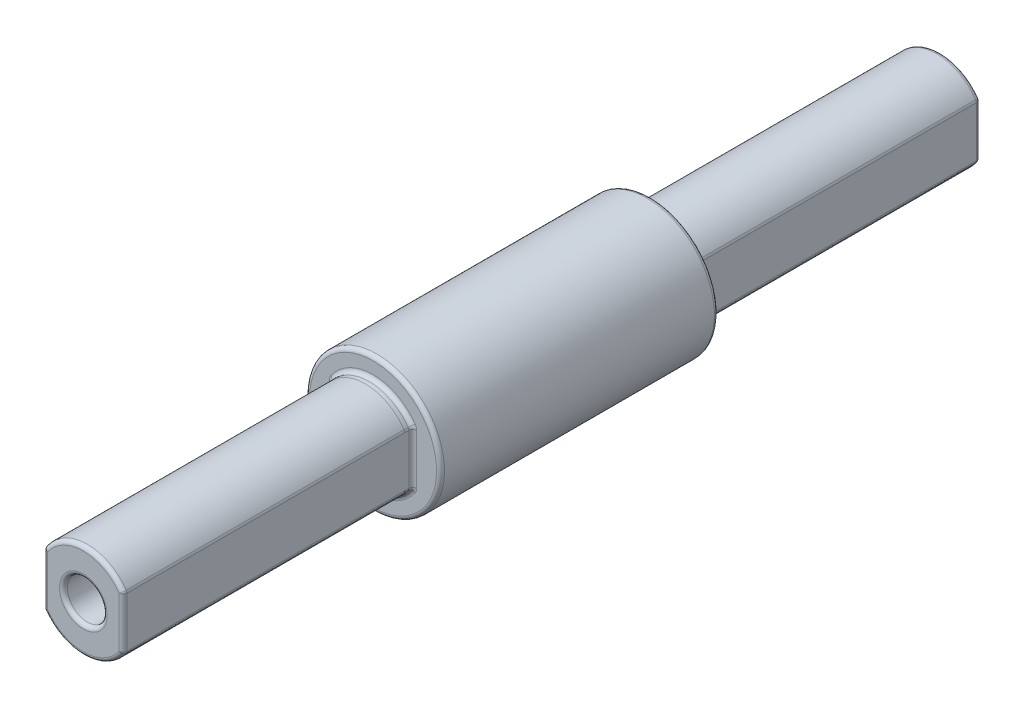
SolidWorks part; units mm, degrees
ref_plane "Alzado" through (0, 0, 0) normal (0, 0, 1) x (1, 0, 0)
ref_plane "Planta" through (0, 0, 0) normal (0, 1, 0) x (1, 0, 0)
ref_plane "Vista lateral" through (0, 0, 0) normal (1, 0, 0) x (0, 0, -1)
sketch "Croquis1" plane through (0, 0, 0) normal (1, 0, 0) x (0, 0, -1)
  line L0 (-55.0748, 0) -> (55.0748, 0) construction
  line L5 (-17.5, 8.5) -> (-17.5, 6)
  line L7 (-54, 6) -> (-54, 2.5)
  line L8 (-54, 2.5) -> (-17.5, 2.5)
  line L9 (0, 0) -> (0, 23.4689) construction
  line L12 (-17.5, 2.5) -> (0, 2.5)
  line L14 (-17.5, 8.5) -> (0, 8.5)
  line L16 (-17.5, 6) -> (-18.5, 6)
  line L17 (-18.5, 6) -> (-54, 6)
  line L18 (0, 8.5) -> (0, 2.5)
  dimension "D1" = 1
  dimension "D2" = 108
  dimension "D3" = 5
  dimension "D4" = 17
  dimension "D5" = 12
  dimension "D6" = 35
revolve "Revolución4" add sketch "Croquis1" angle 360 about L0
sketch "Croquis2" plane through (0, 0, 0) normal (1, 0, 0) x (0, 0, -1)
  line L0 (-18.5, -6) -> (-18.5, 6)
  line L2 (-54, -6) -> (-17.5, -6) construction
  point P3 (-18.5, 0)
split line "Línea de partición1"
sketch "Croquis3" plane through (0, 0, 54) normal (0, 0, 1) x (1, 0, 0)
  line L1 (-5, 3.3166) -> (5, 3.3166) construction
  line L2 (-5, 3.3166) -> (-5, -3.3166)
  line L3 (-5, -3.3166) -> (5, -3.3166) construction
  line L4 (5, 3.3166) -> (5, -3.3166)
  line L5 (-5, 3.3166) -> (5, -3.3166) construction
  line L6 (-5, -3.3166) -> (5, 3.3166) construction
  circle A0 centre (0, 0) radius 6 construction
  circle A1 centre (0, 0) radius 6 construction
  arc A2 (-5, 3.3166) -> (-5, -3.3166) centre (0, 0) ccw
  arc A3 (5, -3.3166) -> (5, 3.3166) centre (0, 0) ccw
  point P0 (0, 0)
  dimension "D1" = 10
extrude "Cortar-Extruir1" cut sketch "Croquis3" against normal up to surface (36.5 mm away) up to face at (6, 0, 17.5)
fillet "Redondeo2" radius 0.5 16 edges at (-5, 0, 17.5) (0, 6, 17.5) (0, -6, 54) (0, -6, 17.5) (0, 6, 54) (-5, 3.3166, 36.25) (-5, 3.3166, 18) (5, 3.3166, 18) (5, 3.3166, 36.25) (5, -3.3166, 36.25) (5, -3.3166, 18) (5, 0, 54) (-5, 0, 54) (5, 0, 17.5) (8.5, 0, 17.5) (2.5, 0, 54)
mirror "Simetría1" about plane through (0, 0, 0) normal (0, 0, 1) of bodies 106
